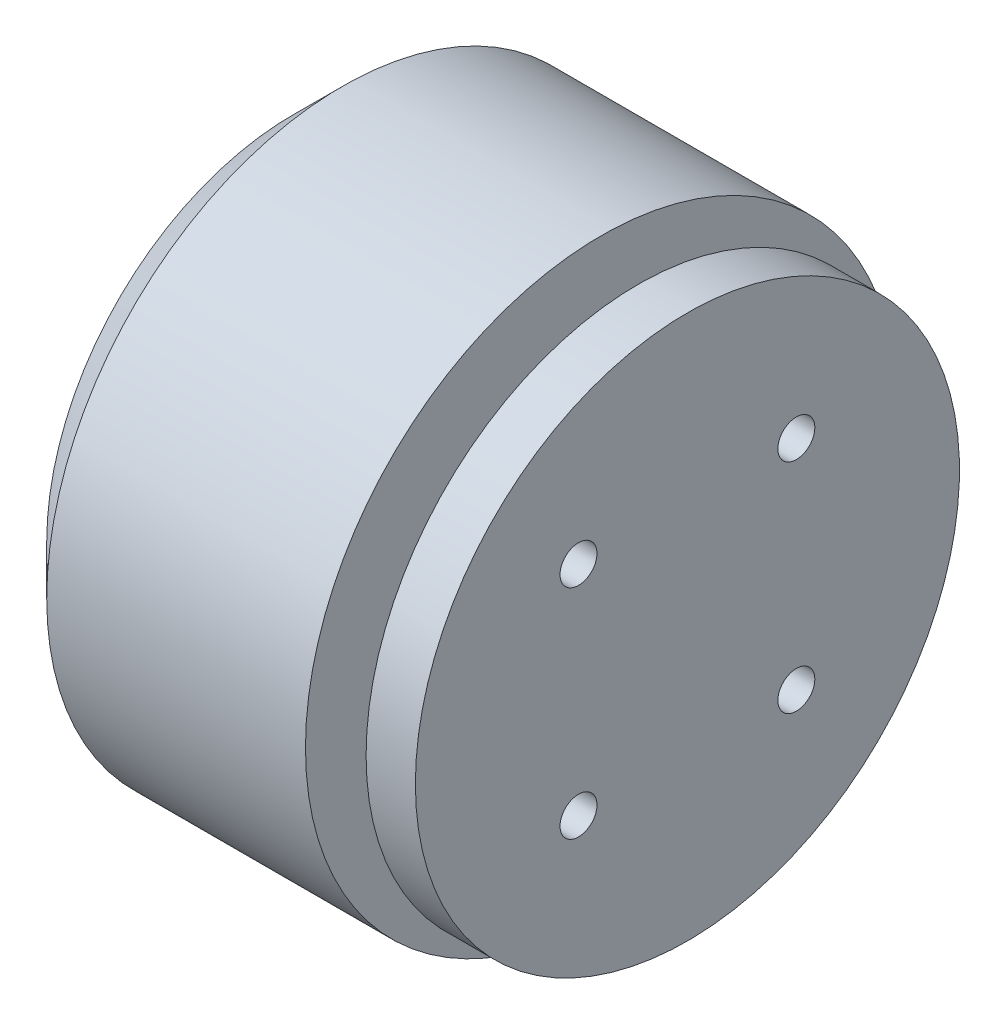
SolidWorks part; units mm, degrees
ref_plane "Front Plane" through (0, 0, 0) normal (0, 0, 1) x (1, 0, 0)
ref_plane "Top Plane" through (0, 0, 0) normal (0, 1, 0) x (1, 0, 0)
ref_plane "Right Plane" through (0, 0, 0) normal (1, 0, 0) x (0, 0, -1)
sketch "Sketch1" plane through (0, 0, 0) normal (0, 0, 1) x (1, 0, 0)
  line L0 (0, 0) -> (0, 22.08)
  line L1 (0, 22.08) -> (-4, 22.08)
  line L2 (-4, 22.08) -> (-4, 16.8)
  line L3 (-4, 16.8) -> (-7, 16.8)
  line L4 (-7, 16.8) -> (-7, 24)
  line L5 (-7, 24) -> (-28, 24)
  line L6 (-28, 24) -> (-32, 20)
  line L7 (-32, 20) -> (-32, 2)
  line L8 (-32, 2) -> (-44, 2)
  line L9 (-44, 2) -> (-44, 0)
  line L10 (-44, 0) -> (0, 0)
  line L11 (-10, 0) -> (1000, 0) construction
revolve "Revolve1" add sketch "Sketch1" angle 360 about L11
sketch "Sketch2" plane through (0, 0, 0) normal (1, 0, 0) x (0, 0, -1)
  circle A0 centre (-8.84, 8.84) radius 1.5
  circle A1 centre (-8.84, -8.84) radius 1.5
  circle A2 centre (8.84, 8.84) radius 1.5
  circle A3 centre (8.84, -8.84) radius 1.5
extrude "Cut-Extrude1" cut sketch "Sketch2" against normal blind 3.3
ref_plane "Plane1" through (-32, 0, 0) normal (1, 0, 0) x (0, 0, -1)
sketch "Sketch3" plane through (-32, 0, 0) normal (1, 0, 0) x (0, 0, -1)
  circle A0 centre (-6, 0) radius 1.5
  circle A1 centre (6, 0) radius 1.5
  circle A2 centre (0, 6) radius 1.5
  circle A3 centre (0, -6) radius 1.5
extrude "Cut-Extrude2" cut sketch "Sketch3" along normal blind 8
